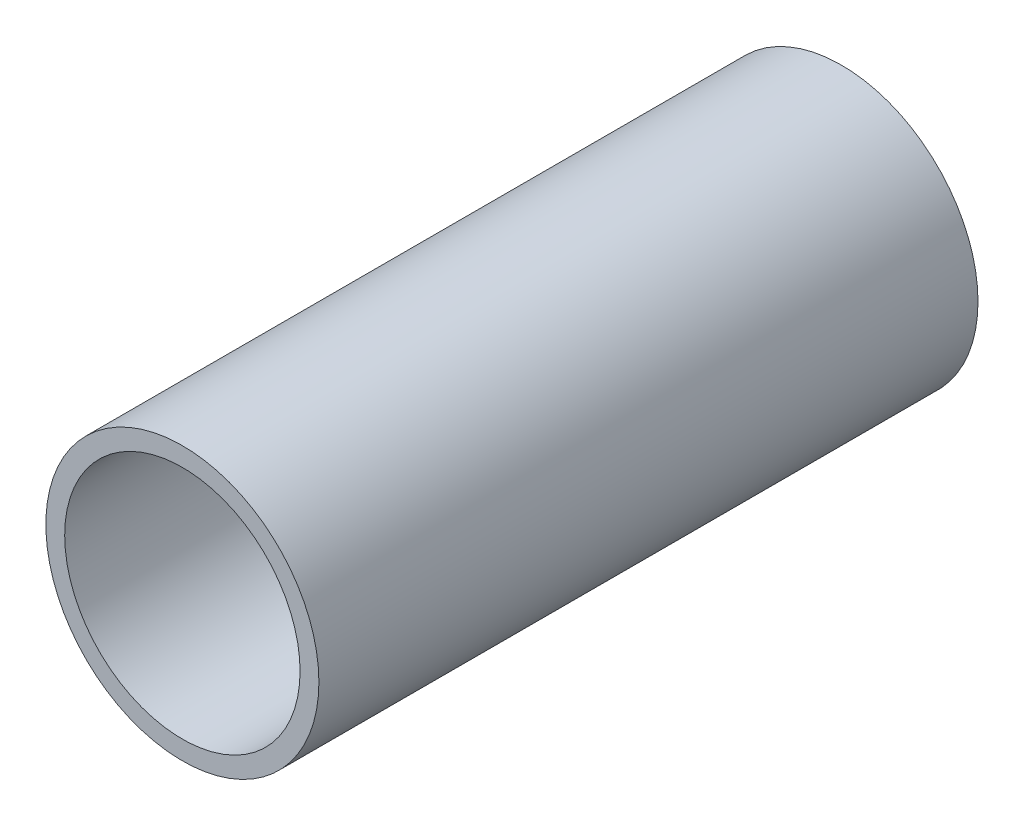
SolidWorks part; units mm, degrees
ref_plane "Front Plane" through (0, 0, 0) normal (0, 0, 1) x (1, 0, 0)
ref_plane "Top Plane" through (0, 0, 0) normal (0, 1, 0) x (1, 0, 0)
ref_plane "Right Plane" through (0, 0, 0) normal (1, 0, 0) x (0, 0, -1)
sketch "Sketch1" plane through (0, 0, 0) normal (0, 0, 1) x (1, 0, 0)
  circle A0 centre (0, 0) radius 12.5
  circle A1 centre (0, 0) radius 14.5
  dimension "D1" = 25
  dimension "D2" = 2
extrude "Boss-Extrude1" add sketch "Sketch1" along normal blind 70
